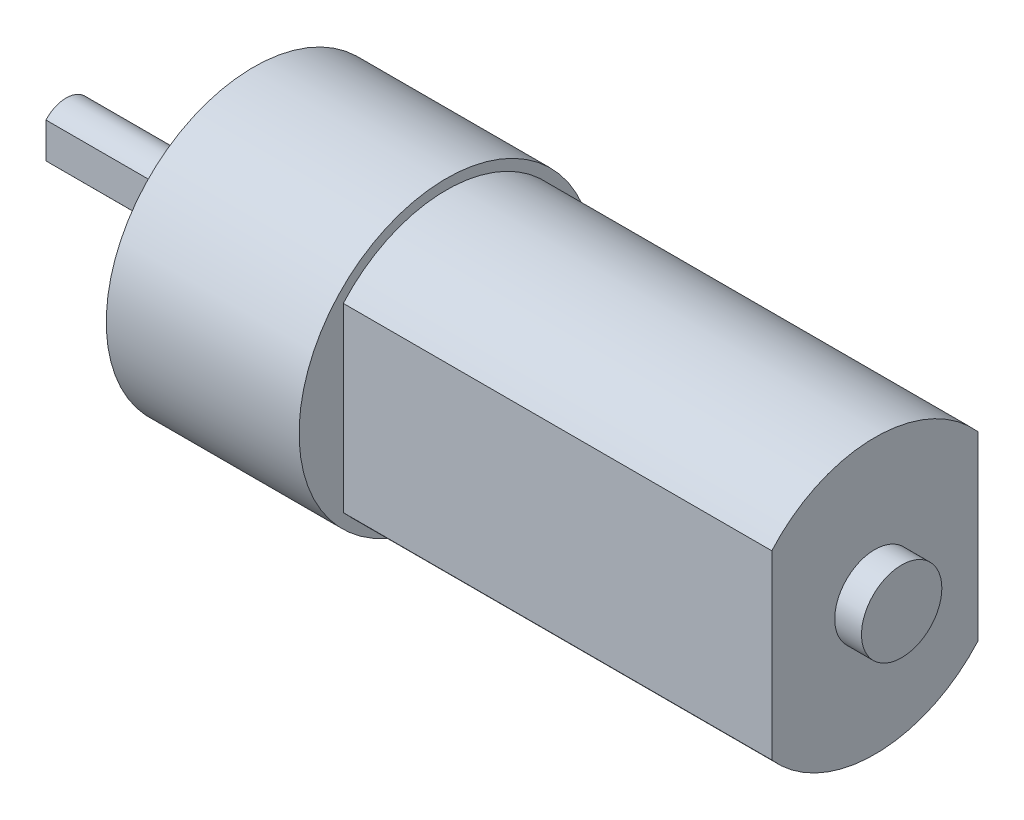
SolidWorks part; units mm, degrees
ref_plane "Plan de face" through (0, 0, 0) normal (0, 0, 1) x (1, 0, 0)
ref_plane "Plan de dessus" through (0, 0, 0) normal (0, 1, 0) x (1, 0, 0)
ref_plane "Plan de droite" through (0, 0, 0) normal (1, 0, 0) x (0, 0, -1)
sketch "Esquisse1" plane through (0, 0, 0) normal (0, 0, 1) x (1, 0, 0)
  line L0 (38.7034, 0) -> (-58.2382, 0) construction
  line L1 (-14, 0) -> (-14, -2)
  line L2 (-14, -2) -> (-3, -2)
  line L3 (-3, -2) -> (-3, -4)
  line L4 (-3, -4) -> (-2, -4)
  line L5 (-2, -4) -> (-2, -7)
  line L6 (-2, -7) -> (0, -7)
  line L7 (0, -7) -> (0, -11)
  line L8 (0, -11) -> (14.4, -11)
  line L9 (14.4, -11) -> (14.4, -10.25)
  line L10 (14.4, -10.25) -> (46.4, -10.25)
  line L11 (46.4, -10.25) -> (46.4, -3)
  line L12 (46.4, -3) -> (48.4, -3)
  line L13 (48.4, -3) -> (48.4, 0)
  line L14 (48.4, 0) -> (-14, 0)
  point P16 (0, -9)
  dimension "D1" = 2
  dimension "D2" = 12
  dimension "D3" = 2
  dimension "D4" = 14.4
  dimension "D5" = 32
  dimension "D6" = 3
  dimension "D7" = 2
  dimension "D8" = 10.25
  dimension "D9" = 11
  dimension "D10" = 7
  dimension "D11" = 4
  dimension "D12" = 1
revolve "Révolution1" add sketch "Esquisse1" angle 360 about L0
sketch "Esquisse2" plane through (46.4, 0, 0) normal (1, 0, 0) x (0, 0, -1)
  line L0 (0, 0) -> (0, -12.8806) construction
  line L1 (-7.7, 11.1958) -> (-7.7, -12.176)
  line L2 (7.7, -12.176) -> (7.7, 11.1958)
  line L3 (-7.7, 11.1958) -> (-16.0203, 11.1958)
  line L4 (-16.0203, 11.1958) -> (-16.0203, -12.176)
  line L5 (-16.0203, -12.176) -> (-7.7, -12.176)
  line L6 (7.7, -12.176) -> (15.6221, -12.176)
  line L7 (15.6221, -12.176) -> (15.6221, 11.1958)
  line L8 (15.6221, 11.1958) -> (7.7, 11.1958)
  dimension "D1" = 15.4
extrude "Enlèv. mat.-Extru.1" cut sketch "Esquisse2" against normal up to surface (32 mm away) up to face at (14.4, 0, -10.25)
sketch "Esquisse3" plane through (-2, 0, 0) normal (-1, 0, 0) x (0, 0, 1)
  line L0 (6.7922, 1.6931) -> (1.6931, 6.7922)
  line L1 (0, 0) -> (-12.3198, 12.3198) construction
  line L2 (-6.7922, -1.6931) -> (-1.6931, -6.7922)
  line L3 (0, 15.4295) -> (0, 0) construction
  circle A0 centre (0, 0) radius 7 construction
  circle A1 centre (0, 0) radius 7 construction
  arc A2 (-6.7922, -1.6931) -> (-1.6931, -6.7922) centre (0, 0) ccw
  arc A3 (1.6931, 6.7922) -> (6.7922, 1.6931) centre (0, 0) cw
extrude "Enlèv. mat.-Extru.2" cut sketch "Esquisse3" against normal up to surface (2 mm away) up to face at (0, 0, -11)
sketch "Esquisse4" plane through (0, 0, 0) normal (-1, 0, 0) x (0, 0, 1)
  line L0 (-10.1299, 0) -> (9.83, 0) construction
  line L1 (0, -9.9871) -> (0, 10.1554) construction
  circle A0 centre (0, 0) radius 9 construction
  circle A1 centre (0, 9) radius 1
  circle A2 centre (-9, 0) radius 1
  circle A3 centre (0, -9) radius 1
  circle A4 centre (9, 0) radius 1
  dimension "D1" = 18
  dimension "D2" = 2
extrude "Enlèv. mat.-Extru.3" cut sketch "Esquisse4" against normal blind 4
sketch "Esquisse5" plane through (-14, 0, 0) normal (-1, 0, 0) x (0, 0, 1)
  line L0 (-2, 5.6753) -> (-2, -4.5548) construction
  line L1 (14.231, 9.3623) -> (1.5, 9.3623)
  line L2 (14.231, 9.3623) -> (14.231, -5.8004)
  line L3 (14.231, -5.8004) -> (1.5, -5.8004)
  line L4 (1.5, 9.3623) -> (1.5, -5.8004)
  circle A0 centre (0, 0) radius 2 construction
  point P6 (-2.3407, -4.5548)
  dimension "D1" = 3.5
extrude "Enlèv. mat.-Extru.4" cut sketch "Esquisse5" against normal blind 8
